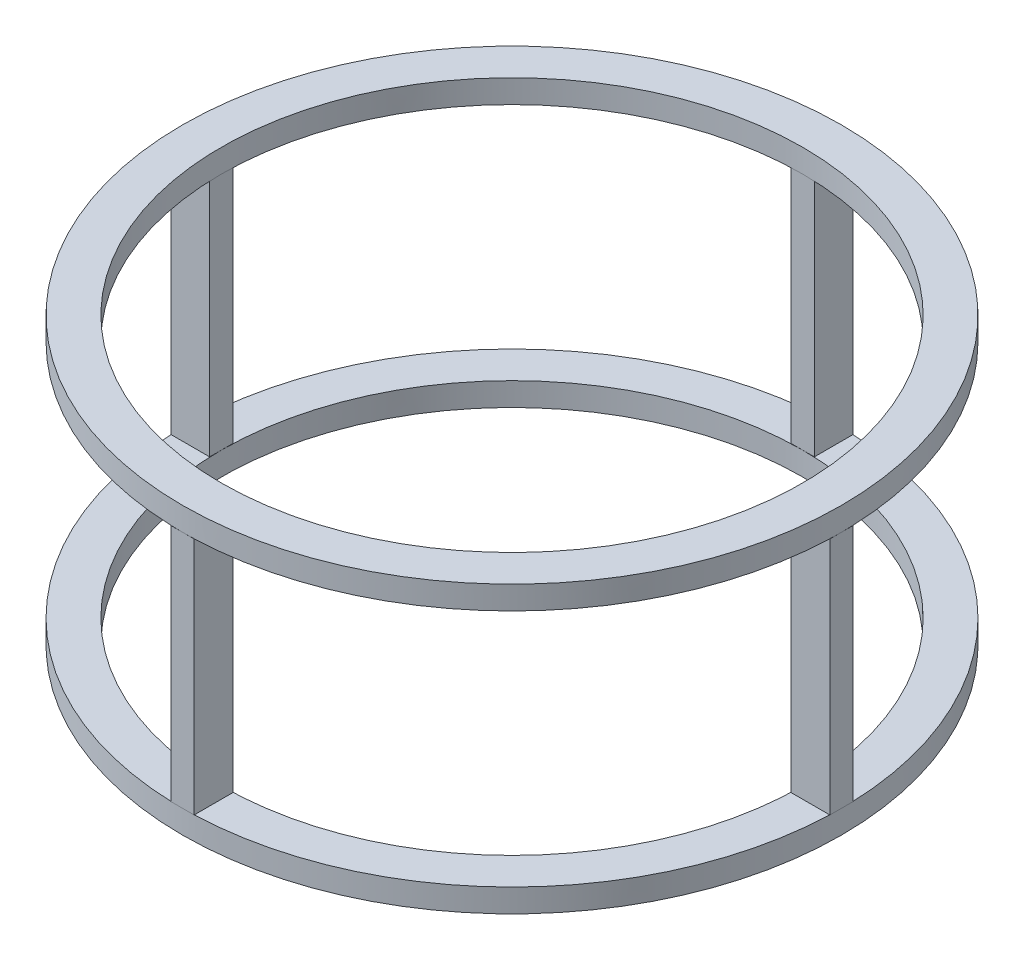
SolidWorks part; units mm, degrees
ref_plane "Front Plane" through (0, 0, 0) normal (0, 0, 1) x (1, 0, 0)
ref_plane "Top Plane" through (0, 0, 0) normal (0, 1, 0) x (1, 0, 0)
ref_plane "Right Plane" through (0, 0, 0) normal (1, 0, 0) x (0, 0, -1)
sketch "Sketch1" plane through (0, 0, 0) normal (0, 1, 0) x (1, 0, 0)
  circle A0 centre (0, 0) radius 53.975
  circle A1 centre (0, 0) radius 47.625
  dimension "D1" = 107.95
  dimension "D2" = 6.35
extrude "Boss-Extrude1" add sketch "Sketch1" along normal blind 3.81
ref_plane "Plane1" through (0, 42.9692, 0) normal (0, 1, 0) x (1, 0, 0)
sketch "Sketch2" plane through (0, 42.9692, 0) normal (0, 1, 0) x (1, 0, 0)
  circle A0 centre (0, 0) radius 53.975
  circle A1 centre (0, 0) radius 53.975 construction
  circle A2 centre (0, 0) radius 47.625
  circle A3 centre (0, 0) radius 47.625 construction
extrude "Boss-Extrude2" add sketch "Sketch2" along normal blind 3.81 separate body
sketch "Sketch4" plane through (0, 0, 0) normal (1, 0, 0) x (0, 0, -1)
  line L0 (53.975, 3.81) -> (-53.975, 3.81) construction
  line L1 (-53.975, 42.9692) -> (-47.625, 42.9692)
  line L2 (-53.975, 42.9692) -> (-53.975, 3.81)
  line L3 (-53.975, 3.81) -> (-47.625, 3.81)
  line L4 (-47.625, 42.9692) -> (-47.625, 3.81)
  dimension "D1" = 6.35
extrude "Boss-Extrude3" add sketch "Sketch4" along normal blind 1.905 and the other way blind 1.905
pattern_circular "CirPattern1" count 4 over 360 about axis through (0, 0, 0) along (0, 1, 0) of "Boss-Extrude3"
